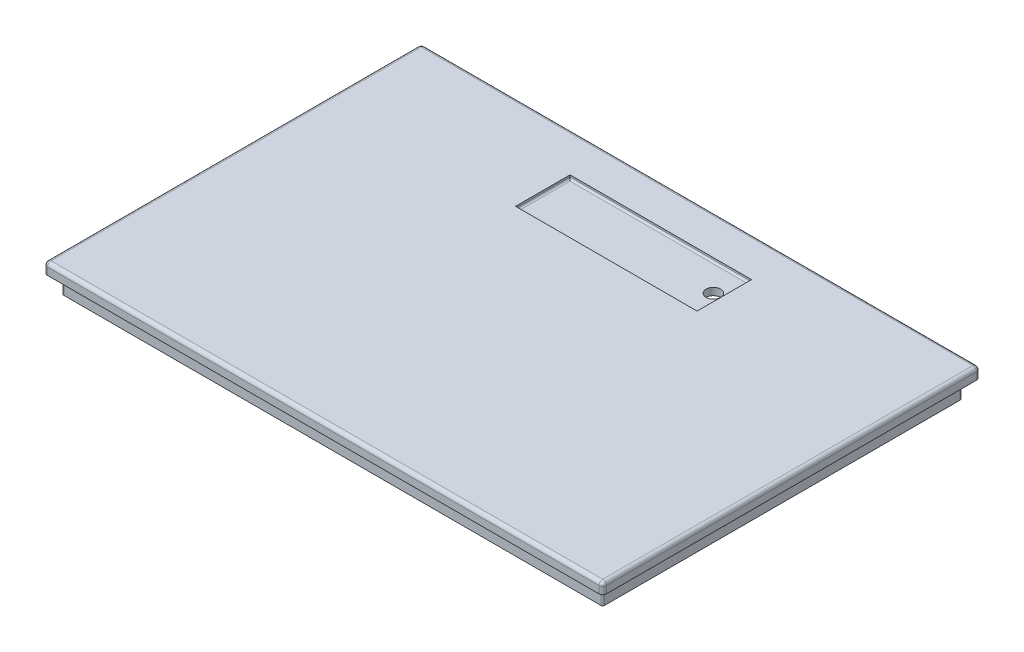
SolidWorks part; units mm, degrees
ref_plane "Front Plane" through (0, 0, 0) normal (0, 0, 1) x (1, 0, 0)
ref_plane "Top Plane" through (0, 0, 0) normal (0, 1, 0) x (1, 0, 0)
ref_plane "Right Plane" through (0, 0, 0) normal (1, 0, 0) x (0, 0, -1)
sketch "Sketch1" plane through (0, 0, 0) normal (0, 1, 0) x (1, 0, 0)
  line L1 (-77, 52) -> (77, 52)
  line L2 (-77, 52) -> (-77, -52)
  line L3 (-77, -52) -> (77, -52)
  line L4 (77, 52) -> (77, -52)
  line L5 (-77, 52) -> (77, -52) construction
  line L6 (-77, -52) -> (77, 52) construction
  point P0 (0, 0)
  dimension "D1" = 104
  dimension "D2" = 154
extrude "Boss-Extrude1" add sketch "Sketch1" along normal blind 3
fillet "Fillet1" radius 1 8 edges at (0, 3, 52) (-77, 3, 0) (0, 3, -52) (77, 3, 0) (-77, 1.5, 52) (77, 1.5, 52) (77, 1.5, -52) (-77, 1.5, -52)
sketch "Sketch2" plane through (0, 0, 0) normal (0, -1, 0) x (1, 0, 0)
  line L1 (-74.5, 49.5) -> (74.5, 49.5)
  line L2 (-74.5, 49.5) -> (-74.5, -49.5)
  line L3 (-74.5, -49.5) -> (74.5, -49.5)
  line L4 (74.5, 49.5) -> (74.5, -49.5)
  line L5 (-74.5, 49.5) -> (74.5, -49.5) construction
  line L6 (-74.5, -49.5) -> (74.5, 49.5) construction
  point P0 (0, 0)
  dimension "D1" = 99
  dimension "D2" = 149
extrude "Extrude-Thin1" add sketch "Sketch2" along normal blind 5 thin
fillet "Fillet2" radius 3 4 edges at (-72.5, 0, 0) (0, 0, 47.5) (72.5, 0, 0) (0, 0, -47.5)
fillet "Fillet3" radius 1 4 edges at (0, -5, -47.5) (72.5, -5, 0) (0, -5, 47.5) (-72.5, -5, 0)
sketch "Sketch3" plane through (-77, 0, 0) normal (-1, 0, 0) x (0, 0, 1)
  line L5 (-6.5, 0) -> (6.5, 0)
  line L7 (49.5, 0) -> (-49.5, 0) construction
  line L8 (-5, 1.5) -> (5, 1.5)
  arc A3 (6.5, 0) -> (5, 1.5) centre (5, 0) ccw
  arc A4 (-6.5, 0) -> (-5, 1.5) centre (-5, 0) cw
  point P11 (0, 0)
  dimension "D2" = 1.5
  dimension "D1" = 10
  dimension "D3" = 1.5
revolve "Cut-Revolve1" cut sketch "Sketch3" angle 90 about L5
sketch "Sketch5" plane through (0, 3, 0) normal (0, 1, 0) x (1, 0, 0)
  line L0 (76, 51) -> (-76, 51) construction
  line L1 (-25, 41) -> (25, 41)
  line L2 (-25, 41) -> (-25, 26)
  line L3 (-25, 26) -> (25, 26)
  line L4 (25, 41) -> (25, 26)
  line L5 (-25, 41) -> (25, 26) construction
  line L6 (-25, 26) -> (25, 41) construction
  point P0 (0, 33.5)
  dimension "D1" = 50
  dimension "D2" = 15
  dimension "D3" = 10
extrude "Cut-Extrude1" cut sketch "Sketch5" against normal blind 1
fillet "Fillet4" radius 0.5 4 edges at (-74.5, -2.5, -49.5) (74.5, -2.5, -49.5) (74.5, -2.5, 49.5) (-74.5, -2.5, 49.5)
sketch "Sketch6" plane through (0, 2, 0) normal (0, 1, 0) x (1, 0, 0)
  line L0 (25, 26) -> (25, 41) construction
  circle A0 centre (22, 33.5) radius 2
  point P4 (25, 33.5)
  dimension "D1" = 4
  dimension "D2" = 3
extrude "Cut-Extrude2" cut sketch "Sketch6" against normal blind 5
fillet "Fillet5" radius 0.5 4 edges at (-25, 2, -33.5) (0, 2, -41) (0, 2, -26) (25, 2, -33.5)
